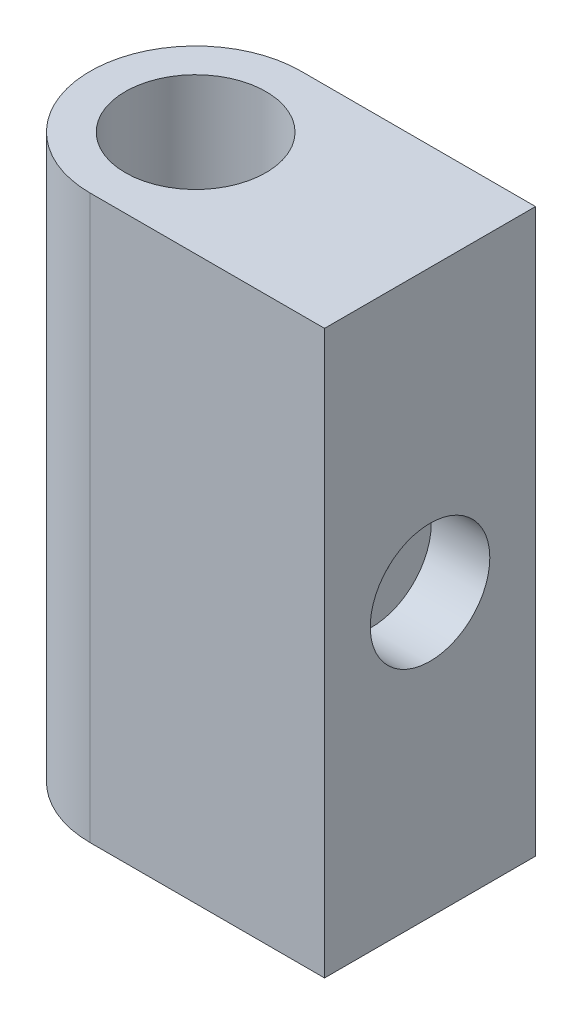
SolidWorks part; units mm, degrees
ref_plane "Front Plane" through (0, 0, 0) normal (0, 0, 1) x (1, 0, 0)
ref_plane "Top Plane" through (0, 0, 0) normal (0, 1, 0) x (1, 0, 0)
ref_plane "Right Plane" through (0, 0, 0) normal (1, 0, 0) x (0, 0, -1)
sketch "Sketch1" plane through (0, 0, 0) normal (0, 1, 0) x (1, 0, 0)
  line L0 (0, 0) -> (0, 5.8529)
  line L1 (0, 4.5) -> (10, 4.5)
  line L2 (0, 4.5) -> (0, -4.5)
  line L3 (0, -4.5) -> (10, -4.5)
  line L4 (10, 4.5) -> (10, -4.5)
  circle A0 centre (0, 0) radius 3
  circle A1 centre (0, 0) radius 4.5
  dimension "D1" = 6
  dimension "D2" = 9
  dimension "D3" = 4.5
  dimension "D4" = 4.5
  dimension "D5" = 0
  dimension "D6" = 10
extrude "Boss-Extrude1" add sketch "Sketch1" along normal blind 24 contours L2 A1 A0 | L2 A1 A0 | A1 L3 L4 L1
sketch "Sketch2" plane through (10, 0, 0) normal (1, 0, 0) x (0, 0, -1)
  line L0 (0, 24) -> (0, 0)
  line L1 (4.5, 24) -> (-4.5, 24) construction
  circle A0 centre (0, 12) radius 2.55
  dimension "D1" = 5.1
extrude "Cut-Extrude1" cut sketch "Sketch2" against normal blind 2.5 contours L0 A0 | L0 A0
sketch "Sketch3" plane through (7.5, 0, 0) normal (1, 0, 0) x (0, 0, -1)
  circle A0 centre (1.987, 10.3927) radius 0.0057
  circle A1 centre (0, 12) radius 2.55 construction
  circle A2 centre (0, 12) radius 2.55
  circle A3 centre (0, 12) radius 1
  dimension "D1" = 2
extrude "Cut-Extrude3" cut sketch "Sketch3" against normal blind 8.5 contours A3
ref_plane "Plane1" through (0.5, 0, 0) normal (1, 0, 0) x (0, 0, -1)
sketch "Sketch4" plane through (0.5, 0, 0) normal (1, 0, 0) x (0, 0, -1)
  circle A1 centre (0, 12) radius 2.55
  circle A2 centre (0, 12) radius 2.55
  dimension "D1" = 0
extrude "Cut-Extrude4" cut sketch "Sketch4" along normal offset from surface (5 mm away) 2 up to face at (7.5, 12, -1)
sketch "Sketch5" plane through (0.5, 0, 0) normal (1, 0, 0) x (0, 0, -1)
  circle A0 centre (0, 12) radius 2.55 construction
  circle A1 centre (0, 12) radius 2.55
extrude "Cut-Extrude5" cut sketch "Sketch5" against normal blind 10
